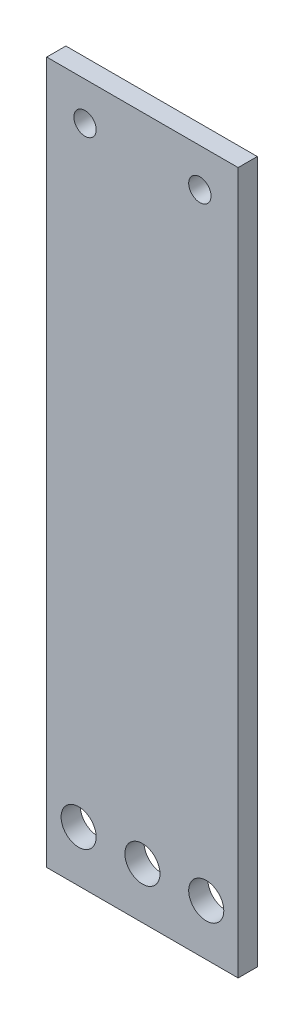
SolidWorks part; units mm, degrees
material "Aluminium"
ref_plane "Front Plane" through (0, 0, 0) normal (0, 0, 1) x (1, 0, 0)
ref_plane "Top Plane" through (0, 0, 0) normal (0, 1, 0) x (1, 0, 0)
ref_plane "Right Plane" through (0, 0, 0) normal (1, 0, 0) x (0, 0, -1)
sketch "Sketch1" plane through (0, 0, 0) normal (0, 0, 1) x (1, 0, 0)
  line L0 (0, 0) -> (0, 8) construction
  line L1 (-15, 0) -> (15, 0)
  line L2 (-15, 0) -> (-15, 110)
  line L3 (-15, 110) -> (15, 110)
  line L4 (15, 0) -> (15, 110)
  line L5 (-10, 8) -> (10, 8) construction
  line L6 (9, 104) -> (-9, 104) construction
  line L7 (0, 104) -> (0, 8) construction
  circle A0 centre (10, 8) radius 2.75
  circle A1 centre (0, 8) radius 2.75
  circle A2 centre (-10, 8) radius 2.75
  circle A3 centre (-9, 104) radius 1.75
  circle A4 centre (9, 104) radius 1.75
  dimension "D3" = 5.5
  dimension "D6" = 3.5
  dimension "D1" = 30
  dimension "D2" = 110
  dimension "D4" = 20
  dimension "D5" = 8
  dimension "D7" = 96
  dimension "D8" = 18
extrude "Boss-Extrude1" add sketch "Sketch1" along normal blind 3
